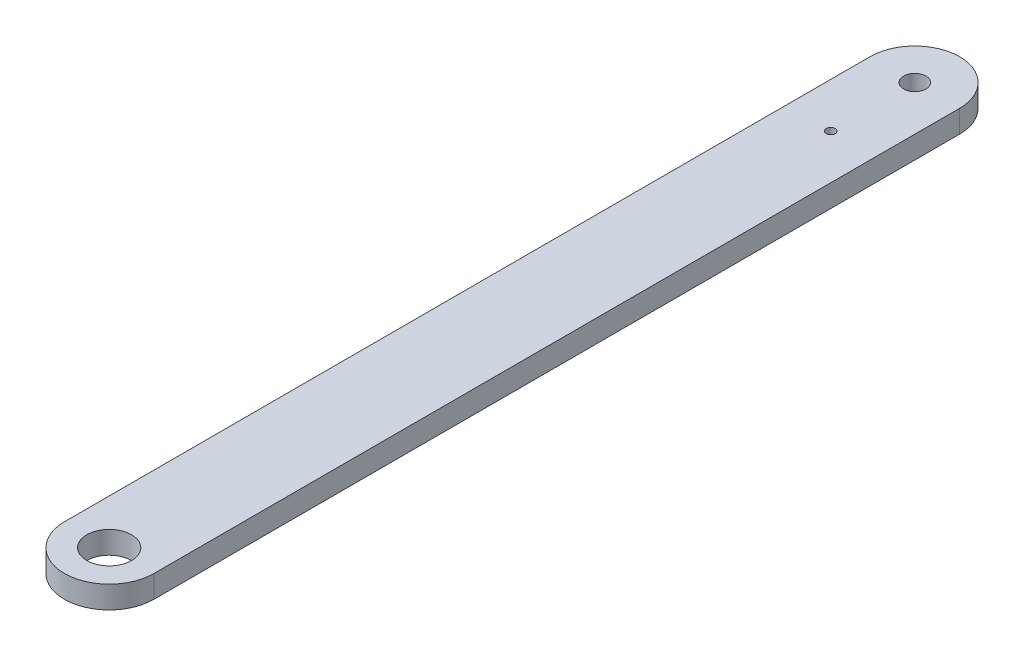
SolidWorks part; units mm, degrees
ref_plane "Front Plane" through (0, 0, 0) normal (0, 0, 1) x (1, 0, 0)
ref_plane "Top Plane" through (0, 0, 0) normal (0, 1, 0) x (1, 0, 0)
ref_plane "Right Plane" through (0, 0, 0) normal (1, 0, 0) x (0, 0, -1)
sketch "Sketch1" plane through (0, 0, 0) normal (0, 1, 0) x (1, 0, 0)
  line L0 (0, 0) -> (49.1133, 0) construction
  line L1 (-10, -90) -> (10, -90)
  line L2 (-10, -90) -> (-10, 90)
  line L3 (-10, 90) -> (10, 90)
  line L4 (10, -90) -> (10, 90)
  line L5 (-10, -90) -> (10, 90) construction
  line L6 (-10, 90) -> (10, -90) construction
  arc A0 (10, 90) -> (-10, 90) centre (0, 90) ccw
  circle A1 centre (0, 90) radius 4 construction
  circle A2 centre (0, 90) radius 2.5
  arc A3 (10, -90) -> (-10, -90) centre (0, -90) cw
  circle A4 centre (0, -90) radius 4 construction
  point P0 (0, 0)
  dimension "D4" = 8
  dimension "D3" = 180
  dimension "D2" = 7.5
  dimension "D5" = 5
extrude "Boss-Extrude1" add sketch "Sketch1" along normal blind 5
sketch "Sketch2" plane through (0, 0, 0) normal (0, -1, 0) x (1, 0, 0)
  circle A0 centre (0, -71.2099) radius 1
  dimension "D1" = 2
extrude "Cut-Extrude1" cut sketch "Sketch2" against normal through all
sketch "Sketch3" plane through (0, 5, 0) normal (0, 1, 0) x (1, 0, 0)
  arc A0 (-10, -90) -> (10, -90) centre (0, -90) ccw construction
  arc A1 (-10, -90) -> (10, -90) centre (0, -90) ccw
  circle A2 centre (0, -90) radius 5
  dimension "D1" = 10
extrude "BearingBore" cut sketch "Sketch3" against normal through all contours A2
